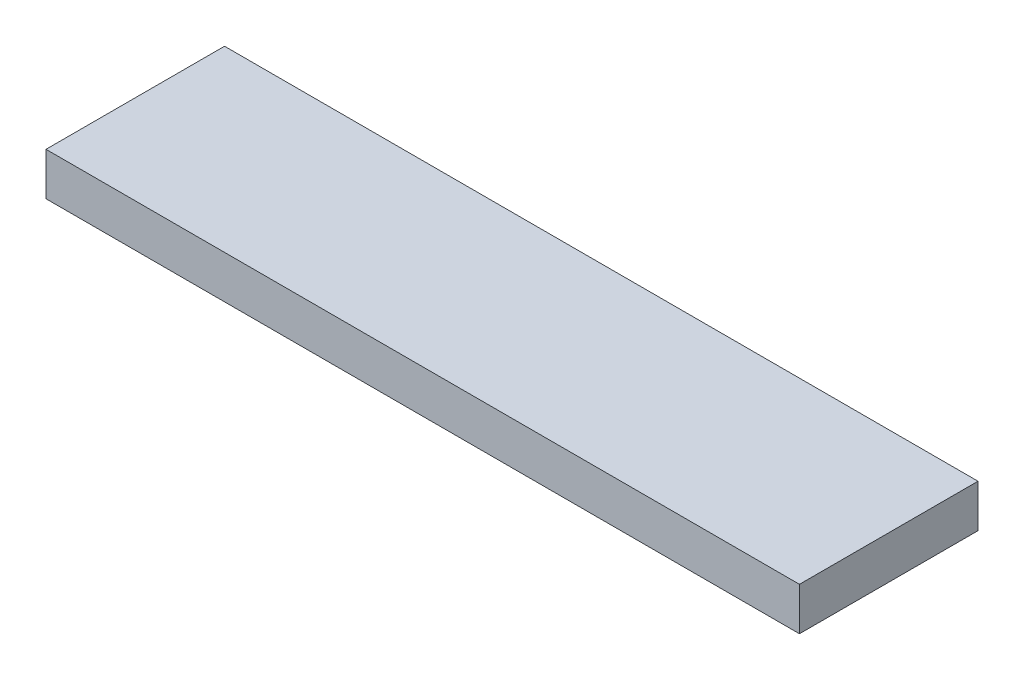
SolidWorks part; units mm, degrees
material "Q355"
ref_plane "前视基准面" through (0, 0, 0) normal (0, 0, 1) x (1, 0, 0)
ref_plane "上视基准面" through (0, 0, 0) normal (0, 1, 0) x (1, 0, 0)
ref_plane "右视基准面" through (0, 0, 0) normal (1, 0, 0) x (0, 0, -1)
sketch "草图1" plane through (0, 0, 0) normal (0, 1, 0) x (1, 0, 0)
  line L1 (-105.5, 25) -> (105.5, 25)
  line L2 (-105.5, 25) -> (-105.5, -25)
  line L3 (-105.5, -25) -> (105.5, -25)
  line L4 (105.5, 25) -> (105.5, -25)
  line L5 (-105.5, 25) -> (105.5, -25) construction
  line L6 (-105.5, -25) -> (105.5, 25) construction
  point P0 (0, 0)
  dimension "D1" = 211
  dimension "D2" = 50
extrude "凸台-拉伸1" add sketch "草图1" along normal blind 12
